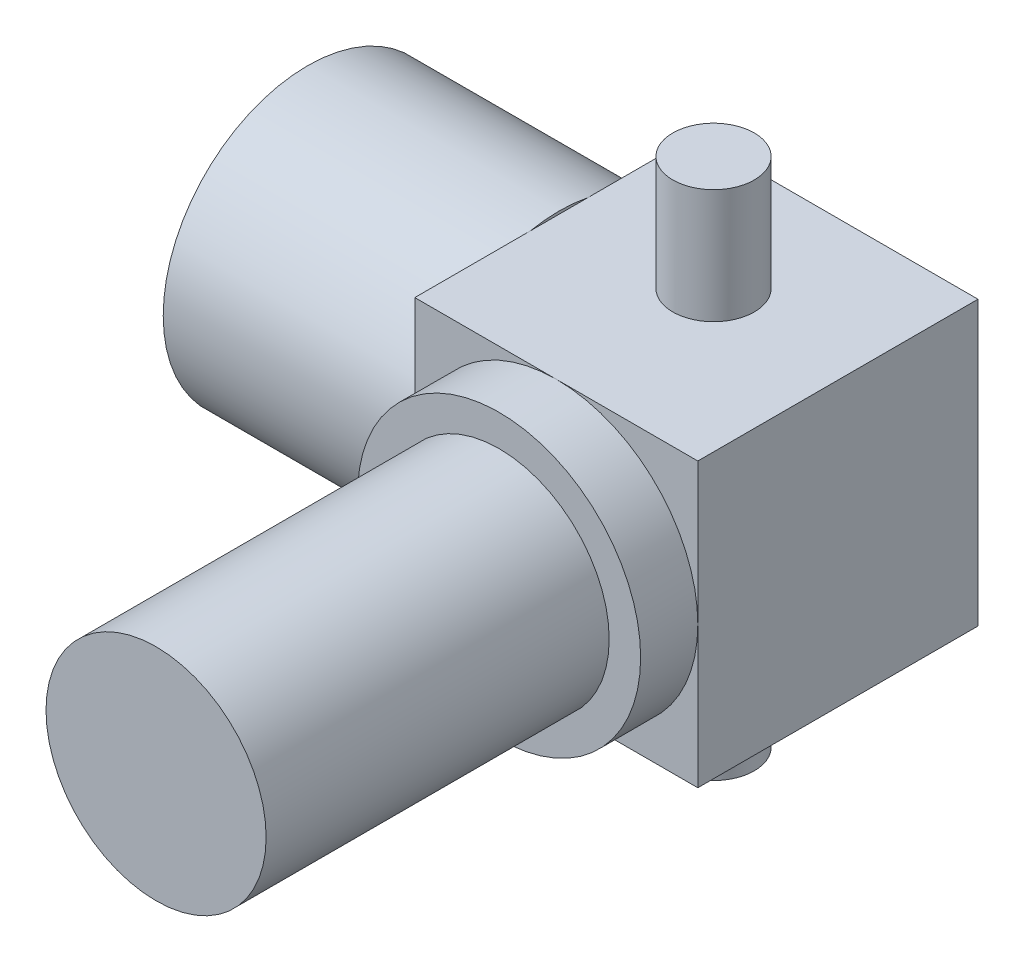
SolidWorks part; units mm, degrees
ref_plane "Front" through (0, 0, 0) normal (0, 0, 1) x (1, 0, 0)
ref_plane "Top" through (0, 0, 0) normal (0, 1, 0) x (1, 0, 0)
ref_plane "Right" through (0, 0, 0) normal (1, 0, 0) x (0, 0, -1)
sketch "Sketch1" plane through (0, 0, 0) normal (0, 0, 1) x (1, 0, 0)
  line L1 (-27.9811, 12.3265) -> (-2.8351, 12.3265)
  line L2 (-27.9811, 12.3265) -> (-27.9811, -12.8195)
  line L3 (-27.9811, -12.8195) -> (-2.8351, -12.8195)
  line L4 (-2.8351, 12.3265) -> (-2.8351, -12.8195)
  dimension "D1" = 25.146
  dimension "D2" = 25.146
extrude "Boss-Extrude1" add sketch "Sketch1" along normal blind 24.892
sketch "Sketch2" plane through (0, 0, 24.892) normal (0, 0, 1) x (1, 0, 0)
  line L0 (-15.4081, 12.3265) -> (-15.4081, -12.8195)
  line L1 (-27.9811, -0.2465) -> (-2.8351, -0.2465)
  line L4 (-27.9811, 12.3265) -> (-27.9811, -12.8195)
  line L5 (-27.9811, -12.8195) -> (-2.8351, -12.8195)
  line L6 (-2.8351, -12.8195) -> (-2.8351, 12.3265)
  line L7 (-2.8351, 12.3265) -> (-27.9811, 12.3265)
  line L8 (-27.9811, 12.3265) -> (-27.9811, -12.8195)
  line L9 (-27.9811, -12.8195) -> (-2.8351, -12.8195)
  line L10 (-2.8351, -12.8195) -> (-2.8351, 12.3265)
  line L11 (-2.8351, 12.3265) -> (-27.9811, 12.3265)
  circle A0 centre (-15.4081, -0.2465) radius 12.573
  dimension "D1" = 0
extrude "Boss-Extrude2" add sketch "Sketch2" along normal blind 5.08 contours L0 A0 L1 | L1 A0 L0 | L0 A0 L1 | L1 A0 L0
sketch "Sketch3" plane through (0, 0, 29.972) normal (0, 0, 1) x (1, 0, 0)
  circle A0 centre (-15.4081, -0.2465) radius 9.779
  circle A1 centre (-15.4081, -0.2465) radius 12.573
  circle A2 centre (-15.4081, -0.2465) radius 12.573
  dimension "D1" = 0
extrude "Boss-Extrude3" add sketch "Sketch3" along normal blind 30.48 contours A0
sketch "Sketch4" plane through (-27.9811, 0, 0) normal (-1, 0, 0) x (0, 0, 1)
  line L0 (24.892, -0.2465) -> (0, -0.2465)
  line L5 (0, 12.3265) -> (0, -12.8195)
  line L6 (0, -12.8195) -> (24.892, -12.8195)
  line L7 (24.892, -12.8195) -> (24.892, -0.2465)
  line L8 (24.892, -0.2465) -> (24.892, 12.3265)
  line L9 (24.892, 12.3265) -> (0, 12.3265)
  line L10 (0, 12.3265) -> (0, -12.8195)
  line L11 (0, -12.8195) -> (24.892, -12.8195)
  line L12 (24.892, -12.8195) -> (24.892, -0.2465)
  line L13 (24.892, -0.2465) -> (24.892, 12.3265)
  line L14 (24.892, 12.3265) -> (0, 12.3265)
  circle A0 centre (12.065, -0.2465) radius 12.827
  dimension "D2" = 25.654
  dimension "D1" = 0
extrude "Boss-Extrude4" add sketch "Sketch4" along normal blind 22.352 contours L0 A0 L14 L10 | L14 A0 | L0 A0 L11 | L10 A0 L0 | L11 A0
sketch "Sketch5" plane through (0, -12.8195, 0) normal (0, -1, 0) x (1, 0, 0)
  line L0 (-15.4081, 0) -> (-15.4081, 10.922)
  line L7 (-27.9811, 0) -> (-2.8351, 0)
  line L8 (-2.8351, 0) -> (-2.8351, 24.892)
  line L9 (-2.8351, 24.892) -> (-15.4081, 24.892)
  line L10 (-15.4081, 24.892) -> (-27.9811, 24.892)
  line L11 (-27.9811, 24.892) -> (-27.9811, 14.605)
  line L12 (-27.9811, 14.605) -> (-27.9811, 9.525)
  line L13 (-27.9811, 9.525) -> (-27.9811, 0)
  line L14 (-27.9811, 0) -> (-2.8351, 0)
  line L15 (-2.8351, 0) -> (-2.8351, 24.892)
  line L16 (-2.8351, 24.892) -> (-15.4081, 24.892)
  line L17 (-15.4081, 24.892) -> (-27.9811, 24.892)
  line L18 (-27.9811, 24.892) -> (-27.9811, 14.605)
  line L19 (-27.9811, 14.605) -> (-27.9811, 9.525)
  line L20 (-27.9811, 9.525) -> (-27.9811, 0)
  circle A0 centre (-15.4081, 10.922) radius 3.6195
  dimension "D2" = 10.922
  dimension "D1" = 0
extrude "Boss-Extrude5" add sketch "Sketch5" along normal blind 10.16
sketch "Sketch6" plane through (0, 12.3265, 0) normal (0, 1, 0) x (1, 0, 0)
  line L0 (-15.4081, 0) -> (-15.4081, -10.922)
  line L7 (-2.8351, 0) -> (-27.9811, 0)
  line L8 (-27.9811, 0) -> (-27.9811, -9.525)
  line L9 (-27.9811, -9.525) -> (-27.9811, -14.605)
  line L10 (-27.9811, -14.605) -> (-27.9811, -24.892)
  line L11 (-27.9811, -24.892) -> (-15.4081, -24.892)
  line L12 (-15.4081, -24.892) -> (-2.8351, -24.892)
  line L13 (-2.8351, -24.892) -> (-2.8351, 0)
  line L14 (-2.8351, 0) -> (-27.9811, 0)
  line L15 (-27.9811, 0) -> (-27.9811, -9.525)
  line L16 (-27.9811, -9.525) -> (-27.9811, -14.605)
  line L17 (-27.9811, -14.605) -> (-27.9811, -24.892)
  line L18 (-27.9811, -24.892) -> (-15.4081, -24.892)
  line L19 (-15.4081, -24.892) -> (-2.8351, -24.892)
  line L20 (-2.8351, -24.892) -> (-2.8351, 0)
  circle A0 centre (-15.4081, -10.922) radius 3.6195
  dimension "D2" = 10.922
  dimension "D1" = 0
extrude "Boss-Extrude6" add sketch "Sketch6" along normal blind 10.16 contours A0
